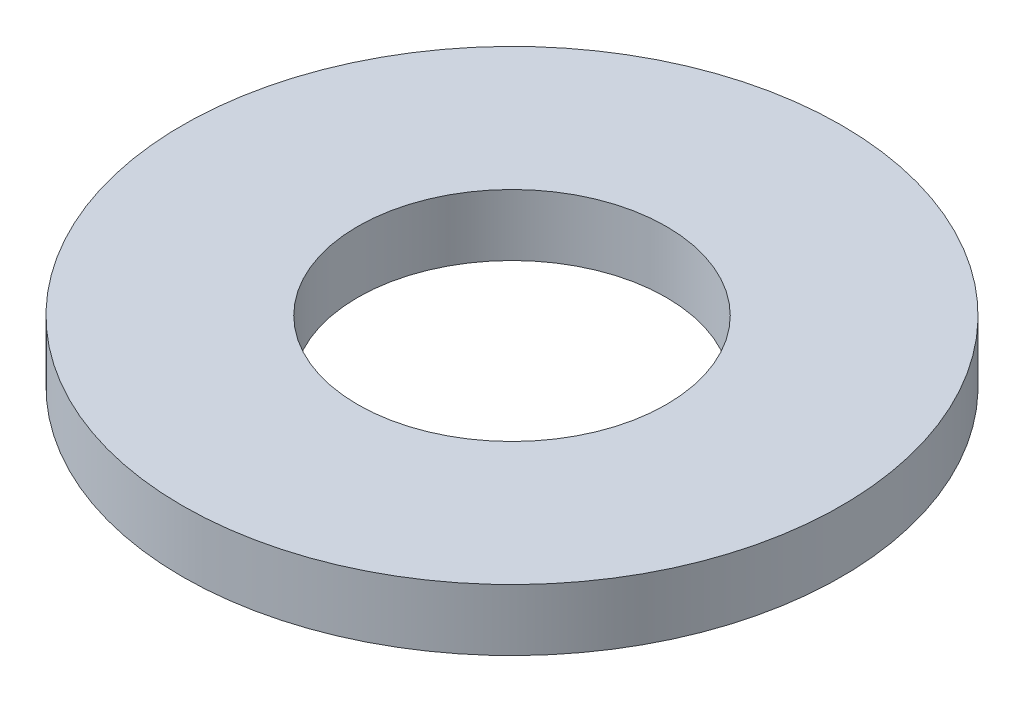
SolidWorks part; units mm, degrees
ref_plane "Front Plane" through (0, 0, 0) normal (0, 0, 1) x (1, 0, 0)
ref_plane "Top Plane" through (0, 0, 0) normal (0, 1, 0) x (1, 0, 0)
ref_plane "Right Plane" through (0, 0, 0) normal (1, 0, 0) x (0, 0, -1)
sketch "Sketch1" plane through (0, 0, 0) normal (0, 1, 0) x (1, 0, 0)
  circle A0 centre (0, 0) radius 7.62
  circle A1 centre (0, 0) radius 3.5687
  dimension "D1" = 15.24
  dimension "D2" = 7.1374
extrude "Boss-Extrude1" add sketch "Sketch1" along normal blind 1.4224
